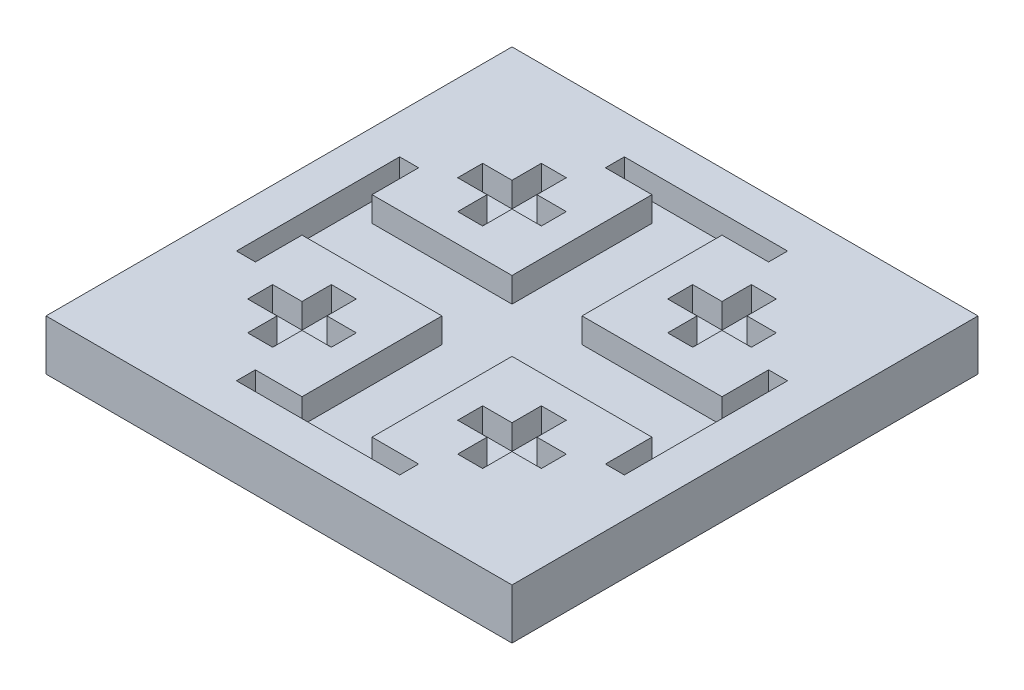
SolidWorks part; units mm, degrees
ref_plane "Front Plane" through (0, 0, 0) normal (0, 0, 1) x (1, 0, 0)
ref_plane "Top Plane" through (0, 0, 0) normal (0, 1, 0) x (1, 0, 0)
ref_plane "Right Plane" through (0, 0, 0) normal (1, 0, 0) x (0, 0, -1)
sketch "Sketch1" plane through (0, 0, 0) normal (0, 1, 0) x (1, 0, 0)
  line L1 (0, 0) -> (47.625, 0)
  line L2 (0, 0) -> (0, 47.625)
  line L3 (0, 47.625) -> (47.625, 47.625)
  line L4 (47.625, 0) -> (47.625, 47.625)
  dimension "D1" = 47.625
extrude "Boss-Extrude1" add sketch "Sketch1" along normal blind 5.15
sketch "Sketch2" plane through (0, 5.15, 0) normal (0, 1, 0) x (1, 0, 0)
  line L1 (20.2341, 27.3909) -> (5.9284, 27.3909)
  line L2 (5.9284, 27.3909) -> (5.9284, 32.1508)
  line L3 (5.9284, 32.1508) -> (3.9904, 32.1508)
  line L4 (3.9904, 32.1508) -> (3.9904, 15.4742)
  line L5 (3.9904, 15.4742) -> (5.9284, 15.4742)
  line L6 (5.9284, 15.4742) -> (5.9284, 20.2341)
  line L7 (5.9284, 20.2341) -> (20.2341, 20.2341)
  line L8 (27.3909, 20.2341) -> (20.2341, 20.2341) construction
  line L9 (27.3909, 20.2341) -> (27.3909, 27.3909) construction
  line L10 (27.3909, 27.3909) -> (20.2341, 27.3909) construction
  line L11 (20.2341, 20.2341) -> (20.2341, 27.3909) construction
  line L13 (27.3909, 27.3909) -> (20.2341, 20.2341) construction
  line L34 (27.3909, 27.3909) -> (27.3909, 41.6966)
  line L35 (13.0813, 34.5437) -> (13.0813, 27.3909) construction
  line L36 (17.3569, 35.8199) -> (17.3569, 33.2676)
  line L37 (17.3569, 33.2676) -> (14.3574, 33.2676)
  line L38 (14.3574, 33.2676) -> (14.3574, 30.2681)
  line L39 (14.3574, 30.2681) -> (11.8051, 30.2681)
  line L40 (11.8051, 30.2681) -> (11.8051, 33.2676)
  line L41 (11.8051, 33.2676) -> (8.8056, 33.2676)
  line L42 (8.8056, 33.2676) -> (8.8056, 35.8199)
  line L43 (8.8056, 35.8199) -> (11.8051, 35.8199)
  line L44 (11.8051, 35.8199) -> (11.8051, 38.8194)
  line L45 (11.8051, 38.8194) -> (14.3574, 38.8194)
  line L46 (14.3574, 38.8194) -> (14.3574, 35.8199)
  line L47 (14.3574, 35.8199) -> (17.3569, 35.8199)
  line L48 (11.8051, 33.2676) -> (14.3574, 35.8199) construction
  line L85 (27.3909, 41.6966) -> (32.1508, 41.6966)
  line L86 (32.1508, 41.6966) -> (32.1508, 43.6346)
  line L87 (32.1508, 43.6346) -> (15.4742, 43.6346)
  line L88 (15.4742, 43.6346) -> (15.4742, 41.6966)
  line L89 (15.4742, 41.6966) -> (20.2341, 41.6966)
  line L90 (20.2341, 41.6966) -> (20.2341, 27.3909)
  line L91 (27.3909, 20.2341) -> (41.6966, 20.2341)
  line L92 (41.6966, 20.2341) -> (41.6966, 15.4742)
  line L93 (41.6966, 15.4742) -> (43.6346, 15.4742)
  line L94 (43.6346, 15.4742) -> (43.6346, 32.1508)
  line L95 (43.6346, 32.1508) -> (41.6966, 32.1508)
  line L96 (41.6966, 32.1508) -> (41.6966, 27.3909)
  line L97 (41.6966, 27.3909) -> (27.3909, 27.3909)
  line L98 (20.2341, 20.2341) -> (20.2341, 5.9284)
  line L99 (20.2341, 5.9284) -> (15.4742, 5.9284)
  line L100 (15.4742, 5.9284) -> (15.4742, 3.9904)
  line L101 (15.4742, 3.9904) -> (32.1508, 3.9904)
  line L102 (32.1508, 3.9904) -> (32.1508, 5.9284)
  line L103 (32.1508, 5.9284) -> (27.3909, 5.9284)
  line L104 (27.3909, 5.9284) -> (27.3909, 20.2341)
  line L105 (20.2341, 34.5437) -> (13.0813, 34.5437) construction
  line L106 (35.8199, 30.2681) -> (33.2676, 30.2681)
  line L107 (33.2676, 30.2681) -> (33.2676, 33.2676)
  line L108 (33.2676, 33.2676) -> (30.2681, 33.2676)
  line L109 (30.2681, 33.2676) -> (30.2681, 35.8199)
  line L110 (30.2681, 35.8199) -> (33.2676, 35.8199)
  line L111 (33.2676, 35.8199) -> (33.2676, 38.8194)
  line L112 (33.2676, 38.8194) -> (35.8199, 38.8194)
  line L113 (35.8199, 38.8194) -> (35.8199, 35.8199)
  line L114 (35.8199, 35.8199) -> (38.8194, 35.8199)
  line L115 (38.8194, 35.8199) -> (38.8194, 33.2676)
  line L116 (38.8194, 33.2676) -> (35.8199, 33.2676)
  line L117 (35.8199, 33.2676) -> (35.8199, 30.2681)
  line L118 (30.2681, 11.8051) -> (30.2681, 14.3574)
  line L119 (30.2681, 14.3574) -> (33.2676, 14.3574)
  line L120 (33.2676, 14.3574) -> (33.2676, 17.3569)
  line L121 (33.2676, 17.3569) -> (35.8199, 17.3569)
  line L122 (35.8199, 17.3569) -> (35.8199, 14.3574)
  line L123 (35.8199, 14.3574) -> (38.8194, 14.3574)
  line L124 (38.8194, 14.3574) -> (38.8194, 11.8051)
  line L125 (38.8194, 11.8051) -> (35.8199, 11.8051)
  line L126 (35.8199, 11.8051) -> (35.8199, 8.8056)
  line L127 (35.8199, 8.8056) -> (33.2676, 8.8056)
  line L128 (33.2676, 8.8056) -> (33.2676, 11.8051)
  line L129 (33.2676, 11.8051) -> (30.2681, 11.8051)
  line L130 (11.8051, 17.3569) -> (14.3574, 17.3569)
  line L131 (14.3574, 17.3569) -> (14.3574, 14.3574)
  line L132 (14.3574, 14.3574) -> (17.3569, 14.3574)
  line L133 (17.3569, 14.3574) -> (17.3569, 11.8051)
  line L134 (17.3569, 11.8051) -> (14.3574, 11.8051)
  line L135 (14.3574, 11.8051) -> (14.3574, 8.8056)
  line L136 (14.3574, 8.8056) -> (11.8051, 8.8056)
  line L137 (11.8051, 8.8056) -> (11.8051, 11.8051)
  line L138 (11.8051, 11.8051) -> (8.8056, 11.8051)
  line L139 (8.8056, 11.8051) -> (8.8056, 14.3574)
  line L140 (8.8056, 14.3574) -> (11.8051, 14.3574)
  line L141 (11.8051, 14.3574) -> (11.8051, 17.3569)
  line L142 (47.625, 23.8125) -> (0, 23.8125) construction
  line L143 (47.625, 0) -> (47.625, 47.625) construction
  line L144 (0, 47.625) -> (0, 0) construction
  point P0 (23.8125, 23.8125)
  point P9 (23.8125, 23.8125)
  point P12 (0, 0)
  point P14 (27.0418, 17.4962)
  point P21 (27.0418, 17.4962)
  point P25 (0, 0)
  point P37 (23.8125, 23.8125)
  point P46 (13.0813, 34.5437)
  point P55 (23.8125, 23.8125)
  point P84 (23.8125, 23.8125)
  point P90 (23.8125, 23.8125)
  point P91 (24.869, 21.5528)
  point P92 (23.7456, 21.5528)
  point P93 (21.5528, 23.8794)
  point P94 (0, 0)
  point P95 (23.2205, 24.4045)
  point P102 (43.1525, 21.9713)
  point P103 (0, 0)
  point P104 (13.5104, 34.1146)
  point P105 (4.3724, 16.4165)
  point P106 (13.3206, 34.8253)
  point P107 (14.061, 36.1163)
  point P108 (0, 0)
  point P109 (43.6346, 32.1508)
  point P110 (27.3909, 20.2341)
  dimension "D1" = 4
  dimension "D2" = 4
extrude "Cut-Extrude1" cut sketch "Sketch2" against normal blind 2.54
equation "\"standard_thickness\"= 5.15mm"
equation "\"D1@Boss-Extrude1\"=\"standard_thickness\""
